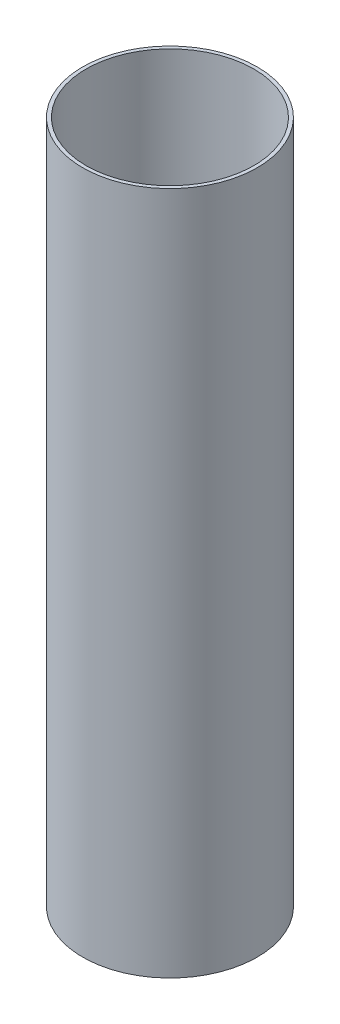
SolidWorks part; units mm, degrees
ref_plane "Front Plane" through (0, 0, 0) normal (0, 0, 1) x (1, 0, 0)
ref_plane "Top Plane" through (0, 0, 0) normal (0, 1, 0) x (1, 0, 0)
ref_plane "Right Plane" through (0, 0, 0) normal (1, 0, 0) x (0, 0, -1)
sketch "Sketch1" plane through (0, 0, 0) normal (0, 0, 1) x (1, 0, 0)
  line L0 (0, 0) -> (0, 304.8) construction
  line L1 (42.672, -43.18) -> (42.672, 304.8)
  line L2 (42.672, 304.8) -> (44.45, 304.8)
  line L3 (44.45, 304.8) -> (44.45, -43.18)
  line L4 (44.45, -43.18) -> (42.672, -43.18)
  dimension "D1" = 347.98
  dimension "D2" = 44.45
  dimension "D3" = 1.778
revolve "Revolve1" add sketch "Sketch1" angle 360 about L0
